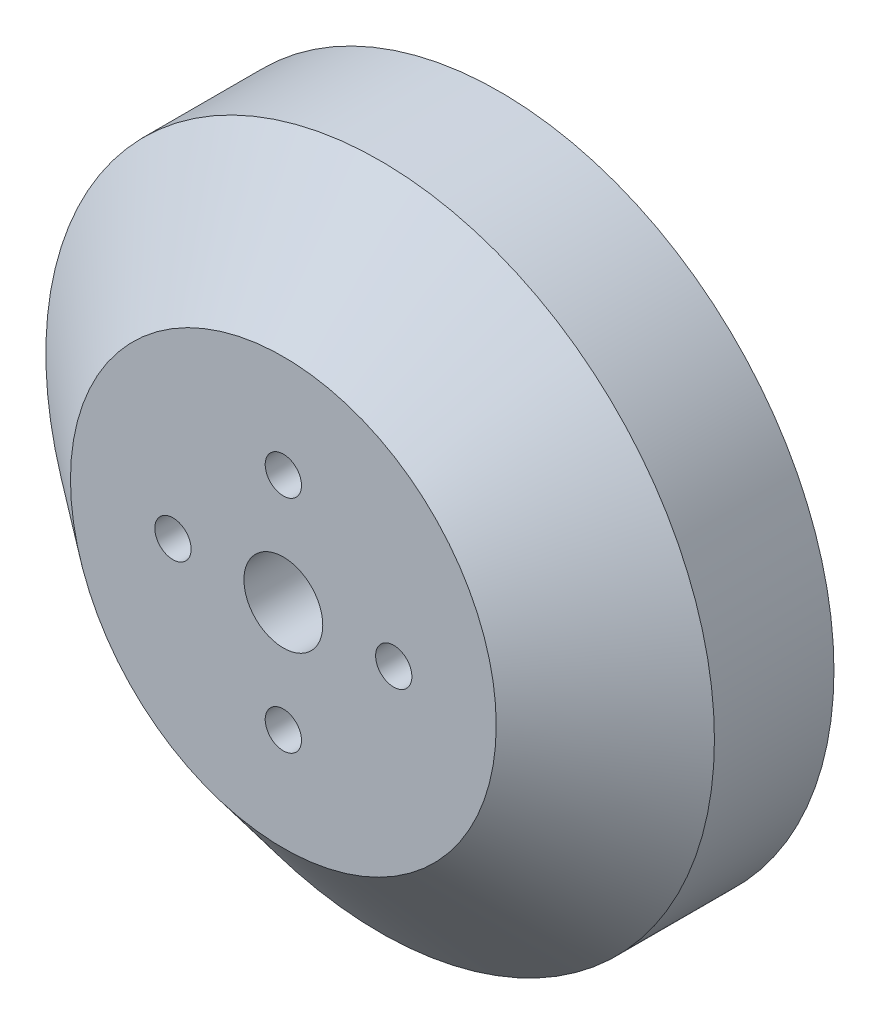
SolidWorks part; units mm, degrees
ref_plane "前视基准面" through (0, 0, 0) normal (0, 0, 1) x (1, 0, 0)
ref_plane "上视基准面" through (0, 0, 0) normal (0, 1, 0) x (1, 0, 0)
ref_plane "右视基准面" through (0, 0, 0) normal (1, 0, 0) x (0, 0, -1)
other "Configuration Table"
sketch "草图1" plane through (0, 0, 0) normal (0, 0, 1) x (1, 0, 0)
  circle A0 centre (0, 0) radius 13.5
  circle A1 centre (0, 0) radius 7 construction
  circle A2 centre (0, 7) radius 1.15
  circle A3 centre (0, -7) radius 1.15
  circle A4 centre (7, 0) radius 1.15
  circle A5 centre (-7, 0) radius 1.15
  circle A6 centre (0, 0) radius 2.5
  dimension "D1" = 27
  dimension "D2" = 14
  dimension "D3" = 2.3
  dimension "D4" = 5
extrude "凸台-拉伸1" add sketch "草图1" along normal blind 7
sketch "草图2" plane through (0, 0, 0) normal (1, 0, 0) x (0, 0, -1)
  line L0 (-7, 13.5) -> (-0.8619, 21.1993)
  line L2 (4.7834, 19.5) -> (0, 13.5)
  line L3 (0, -13.5) -> (0, 13.5) construction
  line L4 (0, 0) -> (27.8481, 0) construction
  line L5 (0, 13.5) -> (-7, 13.5)
  line L7 (-0.8619, 21.1993) -> (6.7179, 21.1993)
  line L9 (4.7834, 19.5) -> (6.7179, 19.5)
  line L10 (6.7179, 21.1993) -> (6.7179, 19.5)
  point P4 (-0.8619, 21.1993)
  dimension "D1" = 6
  dimension "D2" = 6.7179
revolve "旋转1" add sketch "草图2" angle 360 about L4
